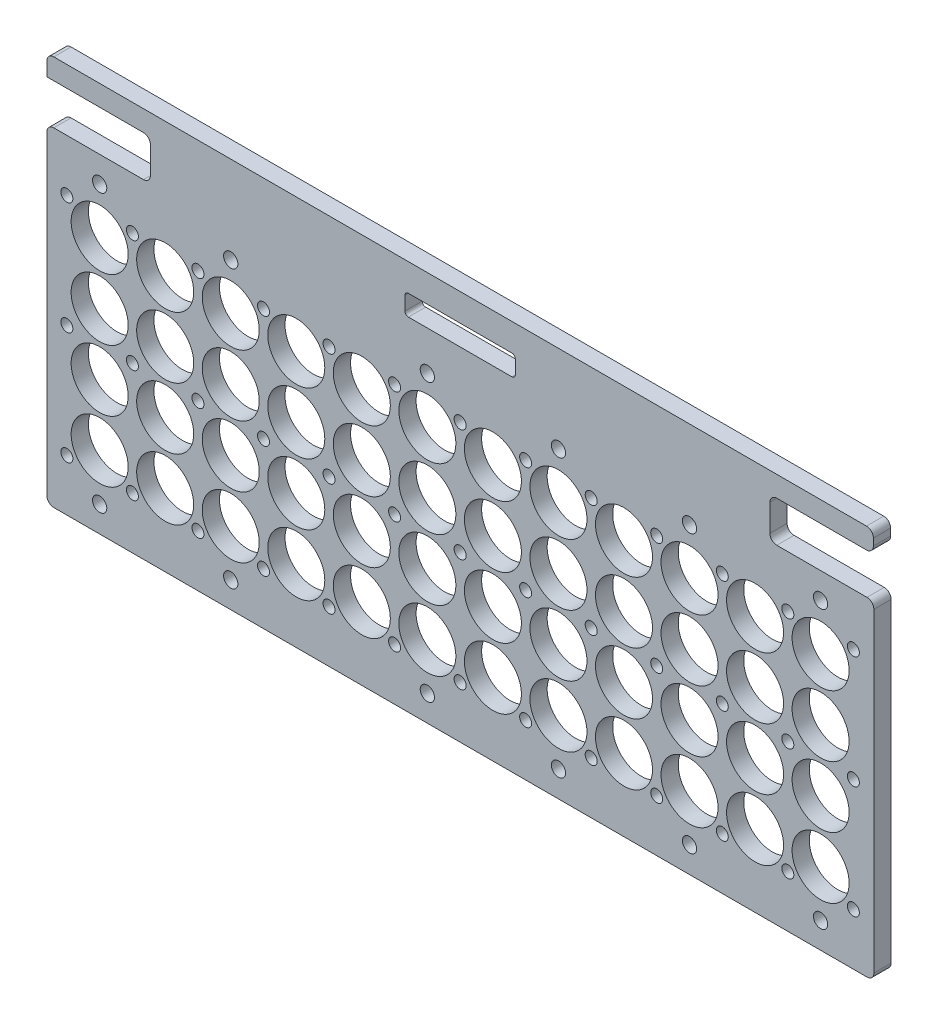
SolidWorks part; units mm, degrees
material "ABS"
ref_plane "X-Y Datum" through (0, 0, 0) normal (0, 0, 1) x (1, 0, 0)
ref_plane "X-Z Datum" through (0, 0, 0) normal (0, 1, 0) x (1, 0, 0)
ref_plane "Y-Z Datum" through (0, 0, 0) normal (1, 0, 0) x (0, 0, -1)
sketch "Sketch1" plane through (0, 0, 0) normal (0, 0, 1) x (1, 0, 0)
  line L1 (-10.2406, 8) -> (78.318, 8)
  line L2 (-10.2406, 8) -> (-10.2406, 16.1972)
  line L7 (-10.2406, 16.1972) -> (78.318, 16.1972)
  line L8 (78.318, 8) -> (78.318, 16.1972)
  line L12 (84.583, 16.1972) -> (87.883, 16.1972) construction
  line L17 (84.583, 4.7) -> (87.883, 4.7) construction
  line L20 (78.318, 0) -> (82.128, 0) construction
  circle A0 centre (0, 0) radius 10.5
  circle A24 centre (0, 0) radius 8 construction
  circle A25 centre (0, 0) radius 4.7 construction
  circle A46 centre (-3.5188, 13.3573) radius 2.5146 construction
  circle A47 centre (-3.5188, 13.3573) radius 1.1913 construction
  circle A78 centre (22.606, 0) radius 10.5
  circle A79 centre (22.606, 0) radius 8 construction
  circle A80 centre (22.606, 0) radius 4.7 construction
  circle A81 centre (45.212, 0) radius 10.5
  circle A82 centre (45.212, 0) radius 8 construction
  circle A83 centre (45.212, 0) radius 4.7 construction
  circle A84 centre (67.818, 0) radius 10.5
  circle A85 centre (67.818, 0) radius 8 construction
  circle A86 centre (67.818, 0) radius 4.7 construction
  circle A87 centre (0, 24.13) radius 10.5
  circle A88 centre (0, 24.13) radius 8 construction
  circle A89 centre (0, 24.13) radius 4.7 construction
  circle A90 centre (22.606, 24.13) radius 10.5
  circle A91 centre (22.606, 24.13) radius 8 construction
  circle A92 centre (22.606, 24.13) radius 4.7 construction
  circle A93 centre (45.212, 24.13) radius 10.5
  circle A94 centre (45.212, 24.13) radius 8 construction
  circle A95 centre (45.212, 24.13) radius 4.7 construction
  circle A96 centre (67.818, 24.13) radius 10.5
  circle A97 centre (67.818, 24.13) radius 8 construction
  circle A98 centre (67.818, 24.13) radius 4.7 construction
  circle A99 centre (0, 48.26) radius 10.5
  circle A100 centre (0, 48.26) radius 8 construction
  circle A101 centre (0, 48.26) radius 4.7 construction
  circle A102 centre (22.606, 48.26) radius 10.5
  circle A103 centre (22.606, 48.26) radius 8 construction
  circle A104 centre (22.606, 48.26) radius 4.7 construction
  circle A105 centre (45.212, 48.26) radius 10.5
  circle A106 centre (45.212, 48.26) radius 8 construction
  circle A107 centre (45.212, 48.26) radius 4.7 construction
  circle A108 centre (67.818, 48.26) radius 10.5
  circle A109 centre (67.818, 48.26) radius 8 construction
  circle A110 centre (67.818, 48.26) radius 4.7 construction
  circle A111 centre (0, 72.39) radius 10.5
  circle A112 centre (0, 72.39) radius 8 construction
  circle A113 centre (0, 72.39) radius 4.7 construction
  circle A114 centre (22.606, 72.39) radius 10.5
  circle A115 centre (22.606, 72.39) radius 8 construction
  circle A116 centre (22.606, 72.39) radius 4.7 construction
  circle A117 centre (45.212, 72.39) radius 10.5
  circle A118 centre (45.212, 72.39) radius 8 construction
  circle A119 centre (45.212, 72.39) radius 4.7 construction
  circle A120 centre (67.818, 72.39) radius 10.5
  circle A121 centre (67.818, 72.39) radius 8 construction
  circle A122 centre (67.818, 72.39) radius 4.7 construction
  circle A123 centre (0, 96.52) radius 10.5
  circle A124 centre (0, 96.52) radius 8 construction
  circle A125 centre (0, 96.52) radius 4.7 construction
  circle A126 centre (22.606, 96.52) radius 10.5
  circle A127 centre (22.606, 96.52) radius 8 construction
  circle A128 centre (22.606, 96.52) radius 4.7 construction
  circle A129 centre (45.212, 96.52) radius 10.5
  circle A130 centre (45.212, 96.52) radius 8 construction
  circle A131 centre (45.212, 96.52) radius 4.7 construction
  circle A132 centre (67.818, 96.52) radius 10.5
  circle A133 centre (67.818, 96.52) radius 8 construction
  circle A134 centre (67.818, 96.52) radius 4.7 construction
  circle A135 centre (0, 120.65) radius 10.5
  circle A136 centre (0, 120.65) radius 8 construction
  circle A137 centre (0, 120.65) radius 4.7 construction
  circle A138 centre (22.606, 120.65) radius 10.5
  circle A139 centre (22.606, 120.65) radius 8 construction
  circle A140 centre (22.606, 120.65) radius 4.7 construction
  circle A141 centre (45.212, 120.65) radius 10.5
  circle A142 centre (45.212, 120.65) radius 8 construction
  circle A143 centre (45.212, 120.65) radius 4.7 construction
  circle A144 centre (67.818, 120.65) radius 10.5
  circle A145 centre (67.818, 120.65) radius 8 construction
  circle A146 centre (67.818, 120.65) radius 4.7 construction
  dimension "D1" = 4
  dimension "D9" = 9.4
  dimension "D4" = 2.5
  dimension "D2" = 6
sketch "Sketch2" plane through (0, 0, 0) normal (0, 0, 1) x (1, 0, 0)
  line L0 (28.8471, 78.318) -> (28.8471, -10.5) construction
  line L5 (4.7, 78.318) -> (19.43, 78.318) construction
  line L6 (4.7, 78.318) -> (4.7, -10.5) construction
  line L7 (4.7, -10.5) -> (19.43, -10.5) construction
  line L8 (19.43, 78.318) -> (19.43, -10.5) construction
  line L9 (28.8471, 78.318) -> (43.5771, 78.318) construction
  line L10 (43.5771, 78.318) -> (43.5771, -10.5) construction
  line L11 (28.8471, -10.5) -> (43.5771, -10.5) construction
  line L12 (52.9942, 78.318) -> (52.9942, -10.5) construction
  line L13 (52.9942, 78.318) -> (67.7242, 78.318) construction
  line L14 (67.7242, 78.318) -> (67.7242, -10.5) construction
  line L15 (52.9942, -10.5) -> (67.7242, -10.5) construction
  line L16 (77.1413, 78.318) -> (77.1413, -10.5) construction
  line L17 (77.1413, 78.318) -> (91.8713, 78.318) construction
  line L18 (91.8713, 78.318) -> (91.8713, -10.5) construction
  line L19 (77.1413, -10.5) -> (91.8713, -10.5) construction
  line L20 (101.2884, 78.318) -> (101.2884, -10.5) construction
  line L21 (101.2884, 78.318) -> (116.0184, 78.318) construction
  line L22 (116.0184, 78.318) -> (116.0184, -10.5) construction
  line L23 (101.2884, -10.5) -> (116.0184, -10.5) construction
  line L24 (125.4355, 78.318) -> (125.4355, -10.5) construction
  line L25 (125.4355, 78.318) -> (140.1655, 78.318) construction
  line L26 (140.1655, 78.318) -> (140.1655, -10.5) construction
  line L27 (125.4355, -10.5) -> (140.1655, -10.5) construction
  line L28 (149.5826, 78.318) -> (149.5826, -10.5) construction
  line L29 (149.5826, 78.318) -> (164.3126, 78.318) construction
  line L30 (164.3126, 78.318) -> (164.3126, -10.5) construction
  line L31 (149.5826, -10.5) -> (164.3126, -10.5) construction
  line L32 (173.7297, 78.318) -> (173.7297, -10.5) construction
  line L33 (173.7297, 78.318) -> (188.4597, 78.318) construction
  line L34 (188.4597, 78.318) -> (188.4597, -10.5) construction
  line L35 (173.7297, -10.5) -> (188.4597, -10.5) construction
  line L36 (197.8768, 78.318) -> (197.8768, -10.5) construction
  line L37 (197.8768, 78.318) -> (212.6068, 78.318) construction
  line L38 (212.6068, 78.318) -> (212.6068, -10.5) construction
  line L39 (197.8768, -10.5) -> (212.6068, -10.5) construction
  line L40 (222.0239, 78.318) -> (222.0239, -10.5) construction
  line L41 (222.0239, 78.318) -> (236.7539, 78.318) construction
  line L42 (236.7539, 78.318) -> (236.7539, -10.5) construction
  line L43 (222.0239, -10.5) -> (236.7539, -10.5) construction
  line L44 (246.171, 78.318) -> (246.171, -10.5) construction
  line L45 (246.171, 78.318) -> (260.901, 78.318) construction
  line L46 (260.901, 78.318) -> (260.901, -10.5) construction
  line L47 (246.171, -10.5) -> (260.901, -10.5) construction
  line L48 (270.3181, 78.318) -> (270.3181, -10.5) construction
  line L49 (270.3181, 78.318) -> (285.0481, 78.318) construction
  line L50 (285.0481, 78.318) -> (285.0481, -10.5) construction
  line L51 (270.3181, -10.5) -> (285.0481, -10.5) construction
  line L52 (-19.43, 78.318) -> (-19.43, -10.5) construction
  line L53 (-19.43, 78.318) -> (-4.7, 78.318) construction
  line L54 (-4.7, 78.318) -> (-4.7, -10.5) construction
  line L55 (-19.43, -10.5) -> (-4.7, -10.5) construction
  line L56 (0, 78.3179) -> (0, 91.526) construction
  line L57 (0, -10.4999) -> (0, -23.708) construction
  line L58 (-27.6439, 33.909) -> (301.0934, 33.909) construction
  line L59 (-19.43, 91.526) -> (285.0481, 91.526) construction
  line L60 (-19.43, 91.526) -> (-19.43, -23.708)
  line L61 (-19.43, -23.708) -> (285.0481, -23.708) construction
  line L62 (285.0481, 91.526) -> (285.0481, -23.708)
  line L63 (-19.43, 91.526) -> (-19.43, 94.447)
  line L64 (-19.43, 94.447) -> (285.0481, 94.447)
  line L65 (285.0481, 94.447) -> (285.0481, 91.526)
  line L66 (-19.43, -23.708) -> (-19.43, -26.629)
  line L67 (-19.43, -26.629) -> (285.0481, -26.629)
  line L68 (285.0481, -26.629) -> (285.0481, -23.708)
  circle A0 centre (0, 0) radius 10.4999
  circle A8 centre (0, 0) radius 4.7 construction
  circle A10 centre (24.13, 0) radius 10.4999
  circle A11 centre (48.26, 0) radius 10.4999
  circle A12 centre (72.39, 0) radius 10.4999
  circle A13 centre (24.13, 22.606) radius 10.4999
  circle A14 centre (48.26, 22.606) radius 10.4999
  circle A15 centre (72.39, 22.606) radius 10.4999
  circle A16 centre (24.13, 45.212) radius 10.4999
  circle A17 centre (48.26, 45.212) radius 10.4999
  circle A18 centre (72.39, 45.212) radius 10.4999
  circle A19 centre (24.13, 67.818) radius 10.4999
  circle A20 centre (48.26, 67.818) radius 10.4999
  circle A21 centre (72.39, 67.818) radius 10.4999
  circle A28 centre (0, 22.606) radius 10.4999
  circle A29 centre (0, 45.212) radius 10.4999
  circle A30 centre (0, 67.818) radius 10.4999
  circle A33 centre (0, 0) radius 8 construction
  circle A34 centre (96.52, 0) radius 10.4999
  circle A35 centre (120.65, 0) radius 10.4999
  circle A36 centre (144.78, 0) radius 10.4999
  circle A37 centre (168.91, 0) radius 10.4999
  circle A38 centre (193.04, 0) radius 10.4999
  circle A39 centre (217.17, 0) radius 10.4999
  circle A40 centre (241.3, 0) radius 10.4999
  circle A41 centre (265.43, 0) radius 10.4999
  circle A42 centre (96.52, 22.606) radius 10.4999
  circle A43 centre (120.65, 22.606) radius 10.4999
  circle A44 centre (144.78, 22.606) radius 10.4999
  circle A45 centre (168.91, 22.606) radius 10.4999
  circle A46 centre (193.04, 22.606) radius 10.4999
  circle A47 centre (217.17, 22.606) radius 10.4999
  circle A48 centre (241.3, 22.606) radius 10.4999
  circle A49 centre (265.43, 22.606) radius 10.4999
  circle A50 centre (96.52, 45.212) radius 10.4999
  circle A51 centre (120.65, 45.212) radius 10.4999
  circle A52 centre (144.78, 45.212) radius 10.4999
  circle A53 centre (168.91, 45.212) radius 10.4999
  circle A54 centre (193.04, 45.212) radius 10.4999
  circle A55 centre (217.17, 45.212) radius 10.4999
  circle A56 centre (241.3, 45.212) radius 10.4999
  circle A57 centre (265.43, 45.212) radius 10.4999
  circle A58 centre (96.52, 67.818) radius 10.4999
  circle A59 centre (120.65, 67.818) radius 10.4999
  circle A60 centre (144.78, 67.818) radius 10.4999
  circle A61 centre (168.91, 67.818) radius 10.4999
  circle A62 centre (193.04, 67.818) radius 10.4999
  circle A63 centre (217.17, 67.818) radius 10.4999
  circle A64 centre (241.3, 67.818) radius 10.4999
  circle A65 centre (265.43, 67.818) radius 10.4999
  circle A82 centre (24.13, 0) radius 8 construction
  circle A83 centre (24.13, 0) radius 4.7 construction
  circle A84 centre (48.26, 0) radius 8 construction
  circle A85 centre (48.26, 0) radius 4.7 construction
  circle A86 centre (72.39, 0) radius 8 construction
  circle A87 centre (72.39, 0) radius 4.7 construction
  circle A88 centre (96.52, 0) radius 8 construction
  circle A89 centre (96.52, 0) radius 4.7 construction
  circle A90 centre (120.65, 0) radius 8 construction
  circle A91 centre (120.65, 0) radius 4.7 construction
  circle A92 centre (144.78, 0) radius 8 construction
  circle A93 centre (144.78, 0) radius 4.7 construction
  circle A94 centre (168.91, 0) radius 8 construction
  circle A95 centre (168.91, 0) radius 4.7 construction
  circle A96 centre (193.04, 0) radius 8 construction
  circle A97 centre (193.04, 0) radius 4.7 construction
  circle A98 centre (217.17, 0) radius 8 construction
  circle A99 centre (217.17, 0) radius 4.7 construction
  circle A100 centre (241.3, 0) radius 8 construction
  circle A101 centre (241.3, 0) radius 4.7 construction
  circle A102 centre (265.43, 0) radius 8 construction
  circle A103 centre (265.43, 0) radius 4.7 construction
  circle A104 centre (24.13, 22.606) radius 8 construction
  circle A105 centre (24.13, 22.606) radius 4.7 construction
  circle A106 centre (48.26, 22.606) radius 8 construction
  circle A107 centre (48.26, 22.606) radius 4.7 construction
  circle A108 centre (72.39, 22.606) radius 8 construction
  circle A109 centre (72.39, 22.606) radius 4.7 construction
  circle A110 centre (96.52, 22.606) radius 8 construction
  circle A111 centre (96.52, 22.606) radius 4.7 construction
  circle A112 centre (120.65, 22.606) radius 8 construction
  circle A113 centre (120.65, 22.606) radius 4.7 construction
  circle A114 centre (144.78, 22.606) radius 8 construction
  circle A115 centre (144.78, 22.606) radius 4.7 construction
  circle A116 centre (168.91, 22.606) radius 8 construction
  circle A117 centre (168.91, 22.606) radius 4.7 construction
  circle A118 centre (193.04, 22.606) radius 8 construction
  circle A119 centre (193.04, 22.606) radius 4.7 construction
  circle A120 centre (217.17, 22.606) radius 8 construction
  circle A121 centre (217.17, 22.606) radius 4.7 construction
  circle A122 centre (241.3, 22.606) radius 8 construction
  circle A123 centre (241.3, 22.606) radius 4.7 construction
  circle A124 centre (265.43, 22.606) radius 8 construction
  circle A125 centre (265.43, 22.606) radius 4.7 construction
  circle A126 centre (24.13, 45.212) radius 8 construction
  circle A127 centre (24.13, 45.212) radius 4.7 construction
  circle A128 centre (48.26, 45.212) radius 8 construction
  circle A129 centre (48.26, 45.212) radius 4.7 construction
  circle A130 centre (72.39, 45.212) radius 8 construction
  circle A131 centre (72.39, 45.212) radius 4.7 construction
  circle A132 centre (96.52, 45.212) radius 8 construction
  circle A133 centre (96.52, 45.212) radius 4.7 construction
  circle A134 centre (120.65, 45.212) radius 8 construction
  circle A135 centre (120.65, 45.212) radius 4.7 construction
  circle A136 centre (144.78, 45.212) radius 8 construction
  circle A137 centre (144.78, 45.212) radius 4.7 construction
  circle A138 centre (168.91, 45.212) radius 8 construction
  circle A139 centre (168.91, 45.212) radius 4.7 construction
  circle A140 centre (193.04, 45.212) radius 8 construction
  circle A141 centre (193.04, 45.212) radius 4.7 construction
  circle A142 centre (217.17, 45.212) radius 8 construction
  circle A143 centre (217.17, 45.212) radius 4.7 construction
  circle A144 centre (241.3, 45.212) radius 8 construction
  circle A145 centre (241.3, 45.212) radius 4.7 construction
  circle A146 centre (265.43, 45.212) radius 8 construction
  circle A147 centre (265.43, 45.212) radius 4.7 construction
  circle A148 centre (24.13, 67.818) radius 8 construction
  circle A149 centre (24.13, 67.818) radius 4.7 construction
  circle A150 centre (48.26, 67.818) radius 8 construction
  circle A151 centre (48.26, 67.818) radius 4.7 construction
  circle A152 centre (72.39, 67.818) radius 8 construction
  circle A153 centre (72.39, 67.818) radius 4.7 construction
  circle A154 centre (96.52, 67.818) radius 8 construction
  circle A155 centre (96.52, 67.818) radius 4.7 construction
  circle A156 centre (120.65, 67.818) radius 8 construction
  circle A157 centre (120.65, 67.818) radius 4.7 construction
  circle A158 centre (144.78, 67.818) radius 8 construction
  circle A159 centre (144.78, 67.818) radius 4.7 construction
  circle A160 centre (168.91, 67.818) radius 8 construction
  circle A161 centre (168.91, 67.818) radius 4.7 construction
  circle A162 centre (193.04, 67.818) radius 8 construction
  circle A163 centre (193.04, 67.818) radius 4.7 construction
  circle A164 centre (217.17, 67.818) radius 8 construction
  circle A165 centre (217.17, 67.818) radius 4.7 construction
  circle A166 centre (241.3, 67.818) radius 8 construction
  circle A167 centre (241.3, 67.818) radius 4.7 construction
  circle A168 centre (265.43, 67.818) radius 8 construction
  circle A169 centre (265.43, 67.818) radius 4.7 construction
  circle A170 centre (0, 22.606) radius 8 construction
  circle A171 centre (0, 22.606) radius 4.7 construction
  circle A172 centre (0, 45.212) radius 8 construction
  circle A173 centre (0, 45.212) radius 4.7 construction
  circle A174 centre (0, 67.818) radius 8 construction
  circle A175 centre (0, 67.818) radius 4.7 construction
  circle A178 centre (0, 84.922) radius 2.625
  circle A181 centre (48.26, 84.922) radius 2.625
  circle A188 centre (217.17, 84.922) radius 2.625
  circle A190 centre (265.43, 84.922) radius 2.625
  circle A191 centre (24.13, 84.922) radius 2.625 [skipped]
  circle A192 centre (72.39, 84.922) radius 2.625 [skipped]
  circle A193 centre (120.65, 84.922) radius 2.625
  circle A194 centre (193.04, 84.922) radius 2.625 [skipped]
  circle A195 centre (241.3, 84.922) radius 2.625 [skipped]
  circle A196 centre (168.91, 84.922) radius 2.625
  circle A197 centre (265.43, -17.104) radius 2.625
  circle A198 centre (217.17, -17.104) radius 2.625
  circle A201 centre (48.26, -17.104) radius 2.625
  circle A202 centre (0, -17.104) radius 2.625
  circle A203 centre (96.52, 84.922) radius 2.625 [skipped]
  circle A204 centre (144.78, 84.922) radius 2.625 [skipped]
  circle A205 centre (168.91, -17.104) radius 2.625
  circle A206 centre (120.65, -17.104) radius 2.625
  dimension "D1" = 12
  dimension "D3" = 12
  dimension "D5" = 12
  dimension "D6" = 17.104
  dimension "D2" = 4
  dimension "D4" = 2
extrude "Boss-Extrude1" add sketch "Sketch2" along normal blind 6.35
sketch "Sketch3" plane through (0, 0, 6.35) normal (0, 0, 1) x (1, 0, 0)
  line L0 (10.4999, 67.818) -> (13.6301, 67.818) construction
  line L1 (4.7, 78.318) -> (19.43, 78.318) construction
  line L2 (4.7, 78.318) -> (4.7, -10.5) construction
  line L3 (4.7, -10.5) -> (19.43, -10.5) construction
  line L4 (19.43, 78.318) -> (19.43, -10.5) construction
  line L5 (12.065, 67.818) -> (12.065, 78.318) construction
  line L6 (4.7, 33.909) -> (19.43, 33.909) construction
  circle A0 centre (0, 0) radius 4.7 construction
  circle A1 centre (0, 0) radius 6.2 construction
  circle A2 centre (0, 67.818) radius 10.4999 construction
  circle A3 centre (24.13, 67.818) radius 10.4999 construction
  circle A4 centre (12.065, 75.3552) radius 4.1656 construction
  circle A5 centre (12.065, 75.3552) radius 2.2098
  circle A6 centre (12.065, -7.5372) radius 2.2098
  circle A7 centre (12.065, -7.5372) radius 4.1656 construction
  circle A32 centre (36.195, 75.3552) radius 2.2098
  circle A33 centre (60.325, 75.3552) radius 2.2098
  circle A34 centre (84.455, 75.3552) radius 2.2098
  circle A35 centre (108.585, 75.3552) radius 2.2098
  circle A36 centre (132.715, 75.3552) radius 2.2098
  circle A37 centre (156.845, 75.3552) radius 2.2098
  circle A38 centre (180.975, 75.3552) radius 2.2098
  circle A39 centre (205.105, 75.3552) radius 2.2098
  circle A40 centre (229.235, 75.3552) radius 2.2098
  circle A41 centre (253.365, 75.3552) radius 2.2098
  circle A42 centre (277.495, 75.3552) radius 2.2098
  circle A43 centre (-12.065, 75.3552) radius 2.2098
  circle A44 centre (277.495, -7.5372) radius 2.2098
  circle A45 centre (253.365, -7.5372) radius 2.2098
  circle A46 centre (229.235, -7.5372) radius 2.2098
  circle A47 centre (205.105, -7.5372) radius 2.2098
  circle A48 centre (180.975, -7.5372) radius 2.2098
  circle A49 centre (156.845, -7.5372) radius 2.2098
  circle A50 centre (132.715, -7.5372) radius 2.2098
  circle A51 centre (108.585, -7.5372) radius 2.2098
  circle A52 centre (84.455, -7.5372) radius 2.2098
  circle A53 centre (60.325, -7.5372) radius 2.2098
  circle A54 centre (36.195, -7.5372) radius 2.2098
  circle A55 centre (-12.065, -7.5372) radius 2.2098
  circle A56 centre (12.065, 33.909) radius 2.2098
  circle A57 centre (36.195, 33.909) radius 2.2098
  circle A58 centre (60.325, 33.909) radius 2.2098
  circle A59 centre (84.455, 33.909) radius 2.2098
  circle A60 centre (108.585, 33.909) radius 2.2098
  circle A61 centre (132.715, 33.909) radius 2.2098
  circle A62 centre (156.845, 33.909) radius 2.2098
  circle A63 centre (180.975, 33.909) radius 2.2098
  circle A64 centre (205.105, 33.909) radius 2.2098
  circle A65 centre (229.235, 33.909) radius 2.2098
  circle A66 centre (253.365, 33.909) radius 2.2098
  circle A67 centre (277.495, 33.909) radius 2.2098
  circle A68 centre (-12.065, 33.909) radius 2.2098
  dimension "D2" = 12
  dimension "D1" = 1.5
  dimension "D3" = 2
extrude "Cut-Extrude1" cut sketch "Sketch3" against normal through all
sketch "Sketch5" plane through (0, 0, 6.35) normal (0, 0, 1) x (1, 0, 0)
  line L1 (-19.43, 94.447) -> (-22.605, 94.447)
  line L2 (-19.43, 94.447) -> (-19.43, -26.629)
  line L3 (-19.43, -26.629) -> (-22.605, -26.629)
  line L4 (-22.605, 94.447) -> (-22.605, -26.629)
  line L5 (285.0481, 94.447) -> (288.2231, 94.447)
  line L6 (285.0481, 94.447) -> (285.0481, -26.629)
  line L7 (285.0481, -26.629) -> (288.2231, -26.629)
  line L8 (288.2231, 94.447) -> (288.2231, -26.629)
extrude "Boss-Extrude2" [suppressed] add sketch "Sketch5" against normal through all
sketch "Sketch6" [suppressed] plane through (0, 0, 6.35) normal (0, 0, 1) x (1, 0, 0)
  line L0 (-10.4999, 67.818) -> (275.9299, 67.818) construction
  circle A0 centre (0, 67.818) radius 10.4999 construction
  circle A1 centre (265.43, 67.818) radius 10.4999 construction
sketch "Sketch7" plane through (0, 0, 6.35) normal (0, 0, 1) x (1, 0, 0)
  line L0 (-19.43, -26.629) -> (0.3535, -26.629) construction
  line L1 (-19.43, -26.629) -> (285.0481, -26.629) construction
  line L10 (-19.43, 33.909) -> (302.2531, 33.909) construction
  line L11 (-19.43, 94.447) -> (-19.43, -26.629) construction
  line L12 (246.76, 93.177) -> (18.67, 93.177)
  line L16 (284.86, 117.064) -> (-19.43, 117.064)
  line L18 (-19.43, 117.064) -> (-19.43, 109.444)
  line L19 (-19.43, 109.444) -> (18.67, 109.444)
  line L20 (18.67, 109.444) -> (18.67, 93.177)
  line L21 (284.86, 117.064) -> (284.86, 109.444)
  line L22 (284.86, 109.444) -> (246.76, 109.444)
  line L23 (246.76, 109.444) -> (246.76, 93.177)
  line L24 (285.0481, 94.447) -> (-19.43, 94.447) construction
  dimension "D1" = 22.617
extrude "Boss-Extrude3" add sketch "Sketch7" against normal through all
sketch "Sketch8" [suppressed] plane through (0, 0, 6.35) normal (0, 0, 1) x (1, 0, 0)
  line L1 (-22.605, 94.447) -> (288.2231, 94.447)
  line L2 (-22.605, 94.447) -> (-22.605, 117.064)
  line L3 (-22.605, 117.064) -> (288.2231, 117.064)
  line L4 (288.2231, 94.447) -> (288.2231, 117.064)
extrude "Boss-Extrude4" [suppressed] add sketch "Sketch8" against normal through all
fillet "Fillet1" radius 2.54 11 edges at (18.67, 109.444, 3.175) (18.67, 94.447, 3.175) (-19.43, 94.447, 3.175) (285.0481, 94.447, 3.175) (246.76, 94.447, 3.175) (246.76, 109.444, 3.175) (284.86, 109.444, 3.175) (285.0481, -26.629, 3.175) (-19.43, -26.629, 3.175) (-19.43, 117.064, 3.175) (284.86, 117.064, 3.175)
fillet "Fillet2" [suppressed] radius 2.54
sketch "Sketch9" plane through (0, 0, 6.35) normal (0, 0, 1) x (1, 0, 0)
  line L0 (10.4999, 67.818) -> (12.065, 67.818) construction
  line L1 (0, 57.3181) -> (0, 55.7119) construction
  line L2 (12.065, 67.818) -> (12.065, 56.515) construction
  line L3 (0, 56.515) -> (12.065, 56.515) construction
  line L5 (48.26, 34.7121) -> (48.26, 33.1059) construction
  line L6 (48.26, 33.909) -> (36.195, 33.909) construction
  line L7 (36.195, 45.212) -> (36.195, 33.909) construction
  line L8 (12.065, 56.515) -> (36.195, 56.515)
  line L9 (12.065, 56.515) -> (12.065, 33.909)
  line L10 (12.065, 33.909) -> (36.195, 33.909)
  line L11 (36.195, 56.515) -> (36.195, 33.909)
  circle A0 centre (0, 67.818) radius 10.4999 construction
  circle A2 centre (0, 45.212) radius 10.4999 construction
  circle A4 centre (48.26, 45.212) radius 10.4999 construction
  circle A5 centre (48.26, 22.606) radius 10.4999 construction
sketch "Sketch10" plane through (0, 0, 6.35) normal (0, 0, 1) x (1, 0, 0)
  line L0 (132.715, 117.064) -> (132.715, 106.9616) construction
  line L1 (282.32, 117.064) -> (-16.89, 117.064) construction
  line L2 (132.715, 106.9616) -> (153.035, 106.9616)
  line L3 (153.035, 106.9616) -> (153.035, 99.3916)
  line L4 (153.035, 99.3916) -> (112.395, 99.3916)
  line L5 (112.395, 99.3916) -> (112.395, 106.9616)
  line L6 (112.395, 106.9616) -> (132.715, 106.9616)
extrude "Cut-Extrude2" cut sketch "Sketch10" against normal through all
fillet "Fillet3" radius 1.27 4 edges at (112.395, 99.3916, 3.175) (153.035, 99.3916, 3.175) (153.035, 106.9616, 3.175) (112.395, 106.9616, 3.175)
